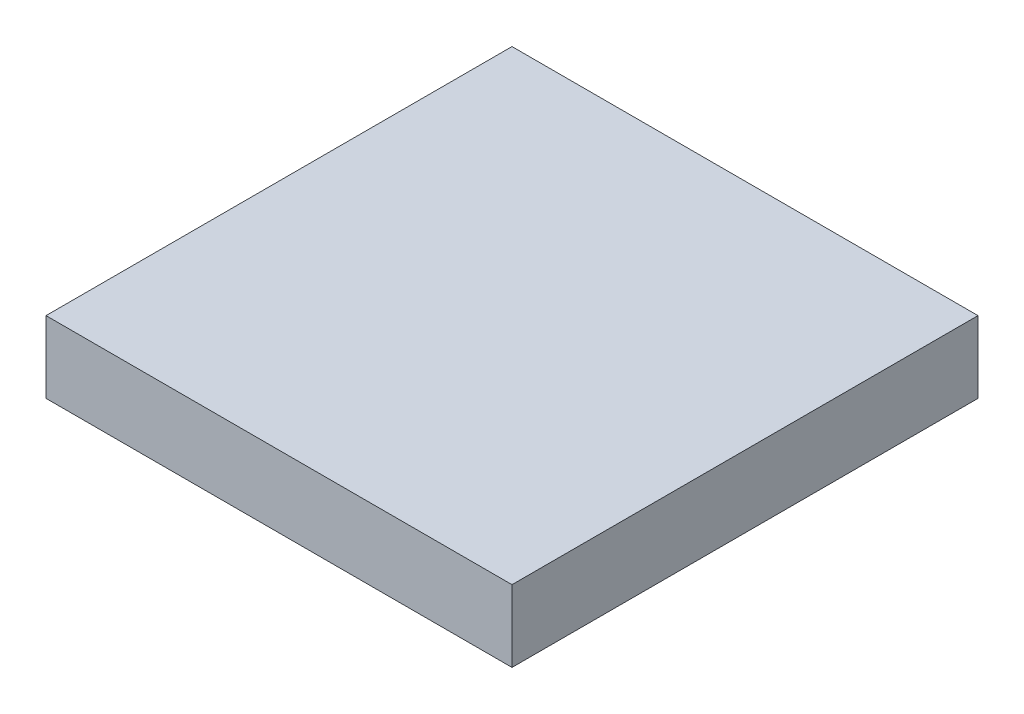
SolidWorks part; units mm, degrees
ref_plane "Front Plane" through (0, 0, 0) normal (0, 0, 1) x (1, 0, 0)
ref_plane "Top Plane" through (0, 0, 0) normal (0, 1, 0) x (1, 0, 0)
ref_plane "Right Plane" through (0, 0, 0) normal (1, 0, 0) x (0, 0, -1)
sketch "Sketch1" plane through (0, 0, 0) normal (0, 1, 0) x (1, 0, 0)
  line L1 (-8.255, -8.255) -> (8.255, -8.255)
  line L2 (-8.255, -8.255) -> (-8.255, 8.255)
  line L3 (-8.255, 8.255) -> (8.255, 8.255)
  line L4 (8.255, -8.255) -> (8.255, 8.255)
  line L5 (-8.255, -8.255) -> (8.255, 8.255) construction
  line L6 (-8.255, 8.255) -> (8.255, -8.255) construction
  point P0 (0, 0)
  dimension "D1" = 16.51
  dimension "D2" = 16.51
extrude "Boss-Extrude1" add sketch "Sketch1" along normal blind 2.54
sketch "Sketch2" plane through (0, 2.54, 0) normal (0, 1, 0) x (1, 0, 0)
  line L0 (-8.255, 8.255) -> (0.127, 8.255) construction
  line L1 (8.255, 8.255) -> (-8.255, 8.255) construction
  line L2 (8.255, -8.255) -> (8.255, 0) construction
  line L3 (8.255, -8.255) -> (8.255, 8.255) construction
  dimension "D1" = 8.382
sketch "Sketch3" plane through (0, 0, 0) normal (0, -1, 0) x (1, 0, 0)
  line L0 (-8.255, -8.255) -> (0.127, -8.255) construction
  line L1 (8.255, 0) -> (8.255, 8.255) construction
  line L2 (0.127, -8.255) -> (0.127, 0) construction
  line L3 (0.127, 0) -> (8.255, 0) construction
  line L4 (-4.445, 8.255) -> (-4.445, -8.255) construction
  line L6 (8.255, 4.445) -> (-8.255, 4.445) construction
  line L7 (-8.255, -8.255) -> (-8.255, 8.255) construction
  line L8 (-8.255, 8.255) -> (8.255, 8.255) construction
  line L14 (-4.953, -5.715) -> (-3.937, -5.715)
  line L19 (2.413, 3.937) -> (5.715, 3.937)
  line L20 (2.413, 3.937) -> (2.413, 4.953)
  line L21 (-4.953, -5.715) -> (-4.953, -2.413)
  line L22 (-4.953, -2.413) -> (-3.937, -2.413)
  line L23 (-3.937, -5.715) -> (-3.937, -2.413)
  line L24 (-4.953, -5.715) -> (-3.937, -2.413) construction
  line L25 (-4.953, -2.413) -> (-3.937, -5.715) construction
  line L26 (2.413, 4.953) -> (5.715, 4.953)
  line L27 (5.715, 3.937) -> (5.715, 4.953)
  line L28 (2.413, 3.937) -> (5.715, 4.953) construction
  line L29 (2.413, 4.953) -> (5.715, 3.937) construction
  point P17 (-4.445, -4.064)
  point P22 (4.064, 4.445)
  dimension "D1" = 3.81
  dimension "D2" = 1.016
  dimension "D3" = 3.302
  dimension "D4" = 3.81
  dimension "D5" = 3.302
  dimension "D6" = 1.016
  dimension "D7" = 2.54
  dimension "D8" = 2.54
extrude "Boss-Extrude2" add sketch "Sketch3" along normal blind 2.032
